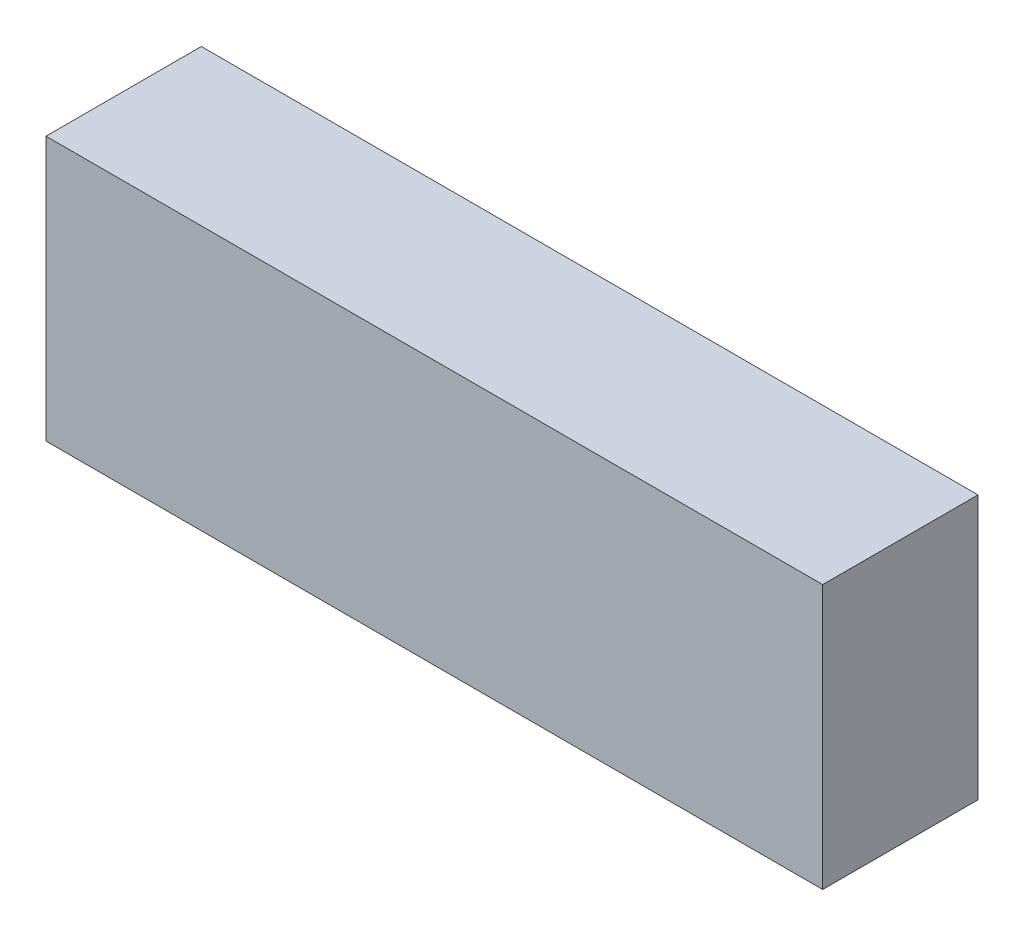
SolidWorks part; units mm, degrees
ref_plane "Front Plane" through (0, 0, 0) normal (0, 0, 1) x (1, 0, 0)
ref_plane "Top Plane" through (0, 0, 0) normal (0, 1, 0) x (1, 0, 0)
ref_plane "Right Plane" through (0, 0, 0) normal (1, 0, 0) x (0, 0, -1)
sketch "Sketch1" plane through (0, 0, 0) normal (0, 0, 1) x (1, 0, 0)
  line L1 (-25, -8.5) -> (25, -8.5)
  line L2 (-25, -8.5) -> (-25, 8.5)
  line L3 (-25, 8.5) -> (25, 8.5)
  line L4 (25, -8.5) -> (25, 8.5)
  line L5 (-25, -8.5) -> (25, 8.5) construction
  line L6 (-25, 8.5) -> (25, -8.5) construction
  point P0 (0, 0)
  dimension "D1" = 50
  dimension "D2" = 17
extrude "Boss-Extrude1" add sketch "Sketch1" along normal mid plane 10
